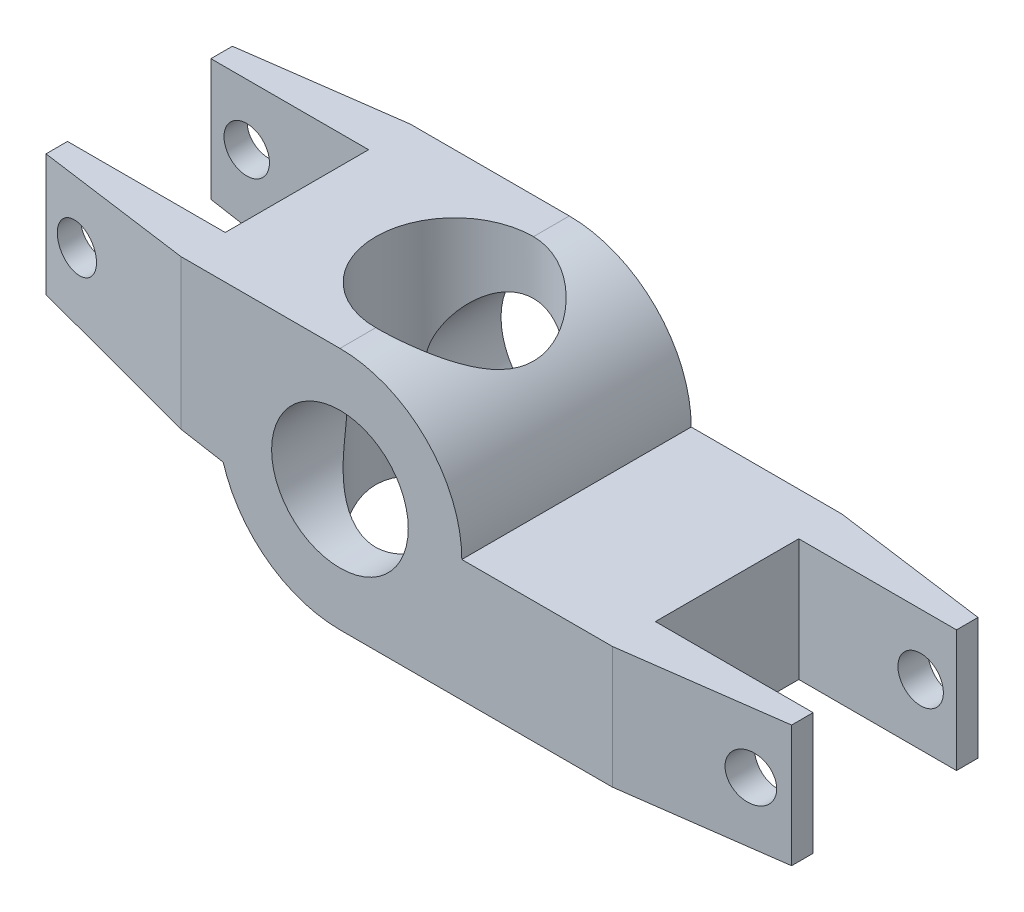
SolidWorks part; units mm, degrees
ref_plane "Front Plane" through (0, 0, 0) normal (0, 0, 1) x (1, 0, 0)
ref_plane "Top Plane" through (0, 0, 0) normal (0, 1, 0) x (1, 0, 0)
ref_plane "Right Plane" through (0, 0, 0) normal (1, 0, 0) x (0, 0, -1)
sketch "Sketch1" plane through (0, 0, 0) normal (0, 0, 1) x (1, 0, 0)
  line L0 (0, -8.5) -> (30, -8.5)
  line L1 (30, -8.5) -> (30, 0)
  line L2 (30, 0) -> (8.5, 0)
  line L3 (0, 8.5) -> (-22, 8.5)
  line L4 (-22, 8.5) -> (-22, 0)
  line L5 (-22, 0) -> (-8.1412, -2.4437)
  circle A0 centre (0, 0) radius 4.765
  circle A1 centre (0, 0) radius 8.5
  dimension "D1" = 9.53
  dimension "D2" = 17
  dimension "D3" = 30
  dimension "D4" = 100
  dimension "D5" = 52
  dimension "D6" = 22
extrude "Boss-Extrude1" add sketch "Sketch1" along normal mid plane 16 contours A1 L3 L4 L5 | A1 A0 | A1 L0 L1 L2
sketch "Sketch2" plane through (0, 8.5, 0) normal (0, 1, 0) x (1, 0, 0)
  line L0 (0, -8) -> (0, 8) construction
  line L2 (0, 8) -> (0, 5.5) construction
  circle A0 centre (0, 0) radius 5.5
  dimension "D1" = 2.5
extrude "Cut-Extrude1" cut sketch "Sketch2" against normal through all
sketch "Sketch5" plane through (0, 8.5, 0) normal (0, 1, 0) x (1, 0, 0)
  line L0 (-11, 8) -> (-22, 5)
  line L1 (0, 8) -> (-22, 8) construction
  line L2 (-22, -8) -> (-22, 8) construction
  line L3 (-11, 8) -> (-22, 8)
  line L4 (-22, 8) -> (-22, 5)
  dimension "D1" = 3
sketch "Sketch7" plane through (0, 8.5, 0) normal (0, 1, 0) x (1, 0, 0)
  line L0 (-8.5, 0) -> (8.5, 0) construction
  line L1 (-22, 5) -> (-11, 5)
  line L2 (-22, 5) -> (-22, -5)
  line L3 (-22, -5) -> (-11, -5)
  line L4 (-11, 5) -> (-11, -5)
  line L5 (-22, 5) -> (-11, -5) construction
  line L6 (-22, -5) -> (-11, 5) construction
  point P4 (-16.5, 0)
  point P6 (-22, 0)
  point P9 (0, 0)
  dimension "D1" = 5
  dimension "D2" = 11
extrude "Cut-Extrude3" cut sketch "Sketch7" against normal blind 16
sketch "Sketch12" plane through (-0.6634, -3.7622, 0) normal (-0.1736, -0.9848, 0) x (0.9848, -0.1736, 0)
  line L0 (-10.5931, 8) -> (-21.6658, 6.5)
  line L1 (-21.6658, 8) -> (-7.5931, 8) construction
  line L2 (-21.6658, 8) -> (-21.6658, 5) construction
  line L3 (-21.6658, 6.5) -> (-21.6658, 8)
  line L4 (-21.6658, 8) -> (-10.5931, 8)
  dimension "D1" = 3
sketch "Sketch13" plane through (0, 8.5, 0) normal (0, 1, 0) x (1, 0, 0)
  line L0 (-22, -6.5) -> (-22, -8)
  line L1 (-22, -8) -> (-22, -5) construction
  line L2 (-11.0956, -8) -> (-22, -8)
  line L3 (-11.0956, -8) -> (-22, -6.5)
  point P5 (-11.0956, -8)
loft "Cut-Loft6" cut profiles "Sketch13", "Sketch12"
mirror "Mirror1" about plane through (0, 0, 0) normal (0, 0, 1) of "Cut-Loft6"
sketch "Sketch14" plane through (0, 0, 0) normal (0, 0, 1) x (1, 0, 0)
  line L0 (-22, 4.25) -> (-11.0956, 4.25) construction
  line L1 (0, -8.5) -> (30, -8.5) construction
  line L2 (30, 0) -> (19.0956, 0)
  line L3 (30, 0) -> (30, -8.5)
  line L4 (-11.0956, -1.9227) -> (-11.0956, 8.5)
  line L5 (-11.0956, 8.5) -> (-22, 8.5)
  line L6 (-22, 8.5) -> (-22, 0)
  line L7 (-22, 0) -> (-11.0956, -1.9227)
  line L8 (-11.0956, -1.9227) -> (-11.0956, 8.5)
  line L9 (-11.0956, 8.5) -> (-22, 8.5)
  line L10 (-22, 8.5) -> (-22, 0)
  line L11 (-22, 0) -> (-11.0956, -1.9227)
  line L12 (30, -8.5) -> (19.0956, -8.5)
  line L13 (19.0956, 0) -> (19.0956, -8.5)
  line L14 (30, 0) -> (19.0956, -8.5) construction
  line L15 (30, -8.5) -> (19.0956, 0) construction
  line L16 (30, -4.25) -> (19.0956, -4.25) construction
  circle A0 centre (-19.5, 4.25) radius 1.585
  circle A1 centre (27.5, -4.25) radius 1.585
  point P12 (24.5478, -4.25)
  dimension "D2" = 3.17
  dimension "D5" = 3.17
  dimension "D3" = 2.5
  dimension "D4" = 2.5
  dimension "D1" = 0
extrude "Cut-Extrude5" cut sketch "Sketch14" against normal mid plane 44 contours A0 | A1
sketch "Sketch15" plane through (0, 0, 0) normal (0, 1, 0) x (1, 0, 0)
  line L0 (30, -8) -> (30, 8) construction
  line L1 (19, 5) -> (30, 5)
  line L2 (19, 5) -> (19, -5)
  line L3 (19, -5) -> (30, -5)
  line L4 (30, 5) -> (30, -5)
  line L5 (19, 5) -> (30, -5) construction
  line L6 (19, -5) -> (30, 5) construction
  line L7 (-11, 5) -> (-22, 5) construction
  line L8 (-22, -5) -> (-11, -5) construction
  line L9 (-22, 0) -> (30, 0) construction
  line L10 (-22, 0) -> (-8.1412, 0) construction
  line L11 (4, 0) -> (4, 8) construction
  line L13 (-11, 8) -> (-22, 5) construction
  line L14 (-22, 8) -> (-22, 5) construction
  line L15 (-11, 8) -> (-22, 8) construction
  line L16 (-11, 8) -> (-22, 5)
  line L17 (-22, 8) -> (-22, 5)
  line L18 (-11, 8) -> (-22, 8)
  line L26 (19, 8) -> (19, 5)
  line L27 (30, 8) -> (8.5, 8) construction
  line L28 (19, -5) -> (19, -8)
  line L29 (19, 8) -> (30, 6.5)
  line L30 (30, 5) -> (30, 8) construction
  line L31 (30, -5) -> (30, -8) construction
  line L32 (30, -8) -> (8.5, -8) construction
  line L33 (19, -8) -> (30, -6.5)
  point P4 (24.5, 0)
extrude "Cut-Extrude6" cut sketch "Sketch15" against normal mid plane 44
